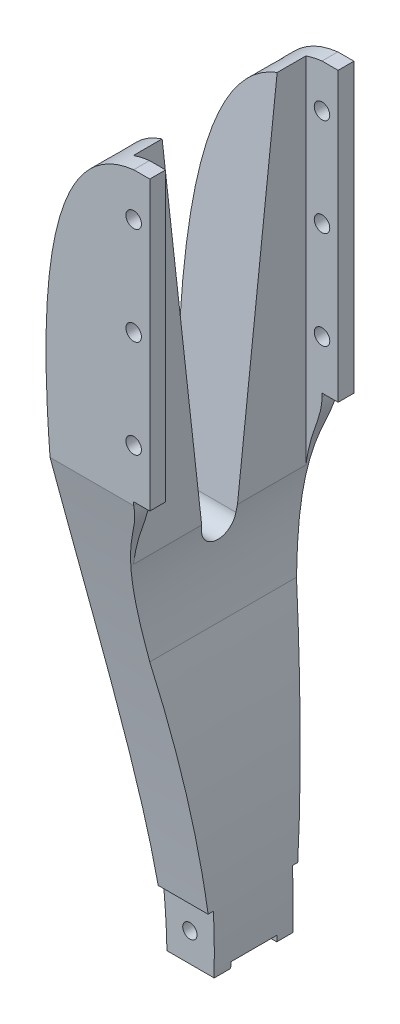
SolidWorks part; units mm, degrees
material "1060-H12"
ref_plane "Front Plane" through (0, 0, 0) normal (0, 0, 1) x (1, 0, 0)
ref_plane "Top Plane" through (0, 0, 0) normal (0, 1, 0) x (1, 0, 0)
ref_plane "Right Plane" through (0, 0, 0) normal (1, 0, 0) x (0, 0, -1)
ref_plane "Plane1" through (0, 35.6, 0) normal (0, 1, 0) x (-1, 0, 0)
sketch "Sketch1" plane through (0, 0, 0) normal (0, 0, 1) x (1, 0, 0)
  line L0 (5.6, 35.6) -> (5.6, -15)
  line L1 (-4.0881, -120.4081) -> (3.5407, -122.8051)
  spline S0 degree 3 poles (5.6, 35.6) (-12.3679, 33.5213) (-8.7824, -50.7826) (5.9542, -91.4515) (-4.0881, -120.4081) knots 0 0 0 0 0.405307 1 1 1 1
  spline S1 degree 2 poles (3.4094, -42.1161) (14.0214, -91.1985) (3.5407, -122.8051) knots 0 0 0 1 1 1
  spline S3 degree 3 poles (5.6, -15) (5.6, -17.2744) (1.6042, -25.848) (2.4158, -35.1136) (3.4094, -42.1161) knots 0 0 0 0 0.227789 0.9215 0.9215 0.9215 0.9215
extrude "Boss-Extrude2" add sketch "Sketch1" along normal blind 35.5
sketch "Sketch3" plane through (0, 0, 0) normal (1, 0, 0) x (0, 0, -1)
  line L0 (0, -14.9824) -> (29.6274, -14.9824)
  line L1 (0, -120.4081) -> (0, 35.6) construction
  line L3 (29.6274, -14.9824) -> (29.6274, -131.5725)
  line L4 (-12.75, -120.4081) -> (-22.7692, -120.4081)
  line L6 (29.6274, -131.5725) -> (-60.5471, -131.5725)
  line L7 (-35.5, 35.6) -> (-35.5, -120.4081) construction
  line L8 (-60.5471, -131.5725) -> (-60.5471, -14.9824)
  line L9 (-60.5471, -14.9824) -> (-35.5, -14.9824)
  spline S0 degree 3 poles (0, -14.9824) (-7.1912, -49.7586) (-11.4412, -85.1664) (-12.75, -120.4081) knots 0 0 0 0 1 1 1 1
  spline S1 degree 3 poles (-35.5, -14.9824) (-28.3088, -49.7586) (-24.078, -85.1664) (-22.7692, -120.4081) knots 0 0 0 0 1 1 1 1
extrude "Cut-Extrude1" cut sketch "Sketch3" against normal mid plane 35.5
sketch "Sketch4" plane through (5.6, 0, 0) normal (1, 0, 0) x (0, 0, -1)
  line L1 (-2.75, 35.6) -> (-32.75, 35.6)
  line L2 (-2.75, 35.6) -> (-2.75, -15)
  line L3 (0, -14.9824) -> (0, 35.6) construction
  line L4 (-32.75, 35.6) -> (-32.75, -15)
  line L5 (-35.4964, -15) -> (-0.0036, -15) construction
  line L8 (-32.75, -15) -> (-32.75, -32.0181)
  line L9 (-32.75, -32.0181) -> (-2.75, -32.0181)
  line L10 (-2.75, -15) -> (-2.75, -32.0181)
  dimension "D1" = 30
  dimension "D2" = 30
  dimension "D3" = 2.75
extrude "Cut-Extrude2" cut sketch "Sketch4" against normal blind 2.8
sketch "Sketch5" plane through (0, 35.6, 0) normal (0, 1, 0) x (1, 0, 0)
  line L1 (5.6, 0) -> (8.4, 0)
  line L2 (5.6, 0) -> (5.6, -2.75)
  line L3 (5.6, -2.75) -> (8.4, -2.75)
  line L4 (8.4, 0) -> (8.4, -2.75)
  line L6 (5.6, -35.5) -> (8.4, -35.5)
  line L7 (5.6, -35.5) -> (5.6, -32.75)
  line L8 (5.6, -32.75) -> (8.4, -32.75)
  line L9 (8.4, -35.5) -> (8.4, -32.75)
  dimension "D1" = 2.8
  dimension "D2" = 2.75
  dimension "D3" = 2.75
  dimension "D4" = 2.8
extrude "Boss-Extrude3" add sketch "Sketch5" against normal blind 50
sketch "Sketch6" plane through (0, 0, 0) normal (1, 0, 0) x (0, 0, -1)
  line L0 (-7.75, 34.9693) -> (-14.7818, -27.8088)
  line L1 (-2.75, 34.9693) -> (-32.75, 34.9693) construction
  line L2 (-20.7446, -27.8076) -> (-27.75, 34.9693)
  line L3 (-7.75, 34.9693) -> (-27.75, 34.9693)
  arc A0 (-20.7446, -27.8076) -> (-14.7818, -27.8088) centre (-17.7631, -27.4748) ccw
  circle A1 centre (0, 0) radius 1
extrude "Cut-Extrude3" cut sketch "Sketch6" against normal mid plane 30
ref_plane "Plane2" through (4.2977, -120.4081, 22.7692) normal (-0.2874, -0.9571, -0.0355) x (0.9578, -0.2872, -0.0107)
hole_wizard "Ø2.7 (2.7) Diameter Hole1" positions "Sketch8" profile "Sketch7" hole size "Ø2.7" standard "ISO" end condition through all
sketch "Sketch8" plane through (0, 0, 35.5) normal (0, 0, 1) x (1, 0, 0)
  line L0 (8.4, -14.4) -> (8.4, 35.6) construction
  line L1 (5.6, 35.6) -> (8.4, 35.6) construction
  point P0 (5.6, 28.1)
  point P1 (5.6, 11.1)
  point P3 (5.6, -5.9)
  dimension "D1" = 2.8
  dimension "D2" = 2.8
  dimension "D3" = 2.8
  dimension "D4" = 41.5
  dimension "D5" = 7.5
  dimension "D6" = 24.5
sketch "Sketch7" plane through (5.6, 28.1, 35.5) normal (1, 0, 0) x (0, -1, 0)
  line L0 (0, 0) -> (0, 35.5)
  line L1 (0, 35.5) -> (1.35, 35.5)
  line L2 (1.35, 35.5) -> (1.35, 0)
  line L5 (1.35, 0) -> (0, 0)
  line L11 (0, -6.35) -> (0, 107.95) construction
  dimension "Thru Hole Dia." = 2.7
  dimension "Thru Hole Depth" = 35.5
hole_wizard "M3 Tapped Hole1" positions "Sketch10" profile "Sketch11" tap size "M3" standard "ISO" end condition through all
sketch "Sketch10" plane through (0, 0, 35.5) normal (0, 0, 1) x (1, 0, 0)
  point P0 (4.5, -85)
sketch "Sketch11" plane through (4.5, -85, 35.5) normal (1, 0, 0) x (0, -1, 0)
  line L0 (0, 0) -> (0, 42.9602)
  line L1 (0, 42.9602) -> (1.25, 42.9602)
  line L2 (1.25, 42.9602) -> (1.25, 0)
  line L5 (1.25, 0) -> (0, 0)
  line L11 (0, -6.35) -> (0, 107.95) construction
  dimension "Thru Tap Drill Dia." = 2.5
  dimension "Thru Tap Drill Depth" = 42.9602
cosmetic thread "Hole Thread1" parameters "D2"=3
sketch "Sketch12" plane through (0, 0, 0) normal (1, 0, 0) x (0, 0, -1)
  line L0 (-9.3959, -80) -> (-10.8927, -80)
  line L1 (-10.8927, -80) -> (-10.8927, -90)
  line L2 (-10.8927, -90) -> (-9.3959, -90)
  line L3 (-9.3959, -90) -> (-9.3959, -80)
  line L4 (-24.6227, -80) -> (-24.6227, -90)
  line L5 (-24.6227, -90) -> (-26.1946, -90)
  line L6 (-26.1946, -90) -> (-26.1946, -80)
  line L7 (-26.1946, -80) -> (-24.6227, -80)
  spline S0 degree 3 poles (0, -14.9824) (-7.1912, -49.7586) (-11.4412, -85.1664) (-12.75, -120.4081) knots 0 0 0 0 1 1 1 1 construction
  spline S1 degree 3 poles (-22.7692, -120.4081) (-24.078, -85.1664) (-28.3088, -49.7586) (-35.5, -14.9824) knots 0 0 0 0 1 1 1 1 construction
  dimension "D1" = 90
  dimension "D2" = 10
extrude "Cut-Extrude4" cut sketch "Sketch12" along normal through all and the other way through all
sketch "Sketch14" plane through (0, 0, 10.8927) normal (0, 0, -1) x (-1, 0, 0)
  line L0 (-8.7203, -90) -> (6.2727, -90)
  line L1 (6.2727, -90) -> (6.2727, -124.0936)
  line L2 (6.2727, -124.0936) -> (-10.5411, -124.0936)
  line L3 (-10.5411, -124.0936) -> (-10.5411, -90)
  line L4 (-10.5411, -90) -> (-8.7203, -90)
extrude "Cut-Extrude5" cut sketch "Sketch14" against normal blind 20
sketch "Sketch15" plane through (0, -90, 0) normal (0, -1, 0) x (-1, 0, 0)
  line L2 (-8.7203, -10.8927) -> (-0.5063, -10.8927) construction
  line L5 (-5.2203, -13.7427) -> (-8.7203, -13.7427)
  line L6 (-8.7203, -24.6227) -> (-8.7203, -10.8927) construction
  line L7 (-5.2203, -21.7427) -> (-9.6234, -21.7427)
  line L8 (-9.6234, -21.7427) -> (-9.6234, -13.7427)
  line L9 (-9.6234, -13.7427) -> (-8.7203, -13.7427)
  arc A0 (-5.2203, -21.7427) -> (-5.2203, -13.7427) centre (-5.2203, -17.7427) ccw
  dimension "D1" = 8
  dimension "D2" = 6.85
  dimension "D3" = 3.5
extrude "Cut-Extrude6" cut sketch "Sketch15" against normal blind 1
sketch "Sketch16" plane through (0, 0, 35.5) normal (0, 0, 1) x (1, 0, 0)
  line L0 (171.0634, 145.588) -> (5.2203, -126.5) construction
